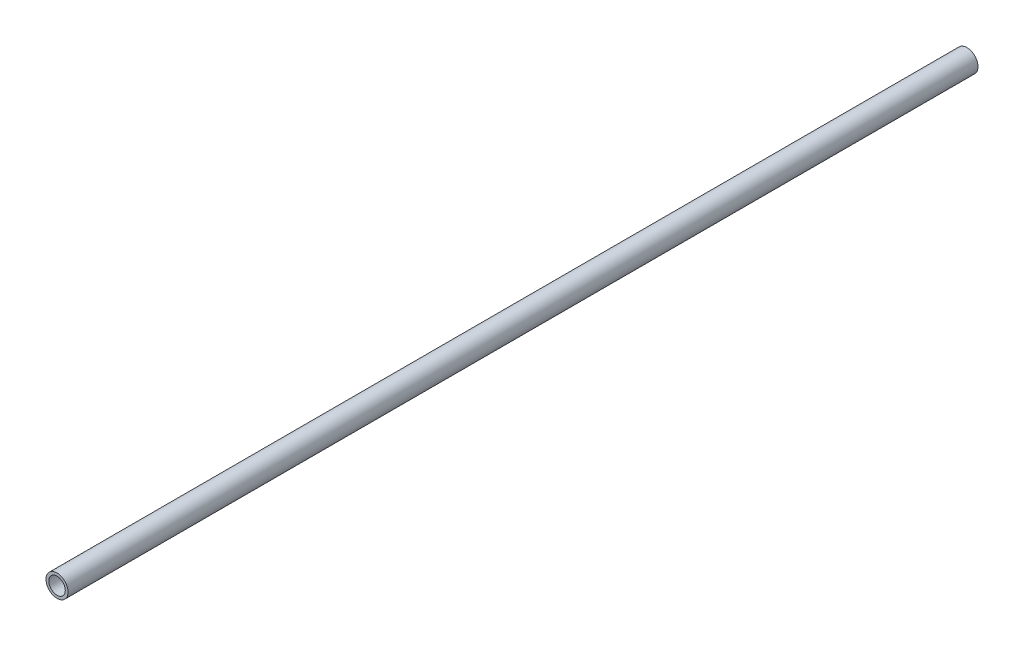
SolidWorks part; units mm, degrees
ref_plane "前视基准面" through (0, 0, 0) normal (0, 0, 1) x (1, 0, 0)
ref_plane "上视基准面" through (0, 0, 0) normal (0, 1, 0) x (1, 0, 0)
ref_plane "右视基准面" through (0, 0, 0) normal (1, 0, 0) x (0, 0, -1)
sketch "草图1" plane through (0, 0, 0) normal (0, 0, 1) x (1, 0, 0)
  circle A0 centre (0, 0) radius 4
  circle A1 centre (0, 0) radius 3
  dimension "D1" = 8
  dimension "D2" = 1
extrude "凸台-拉伸1" add sketch "草图1" along normal blind 330
